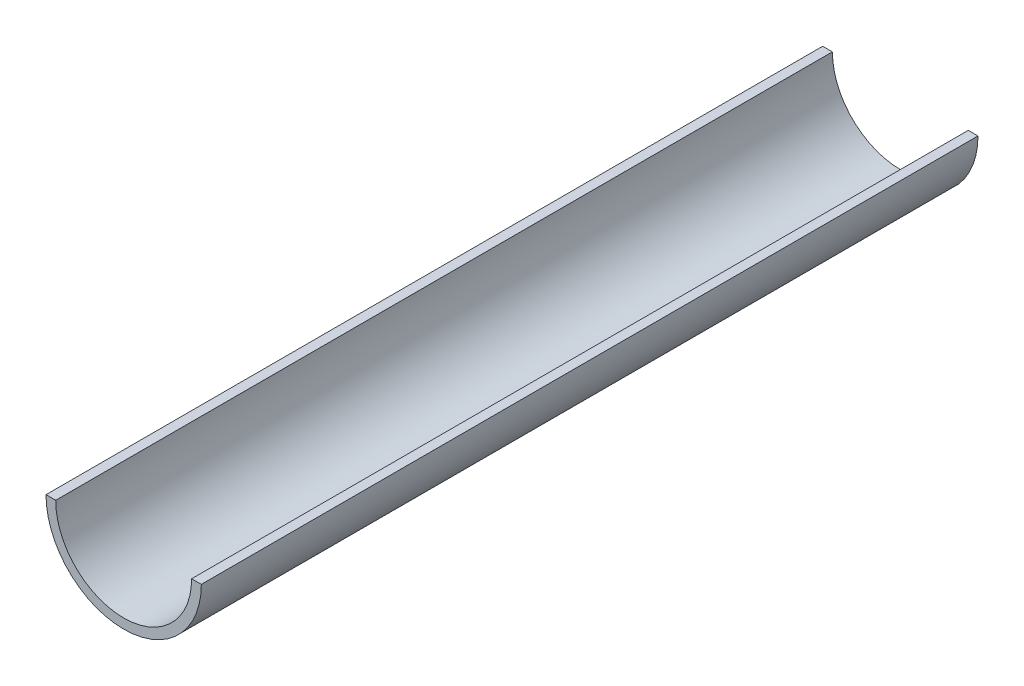
SolidWorks part; units mm, degrees
material "Acrylic (Medium-high impact)"
ref_plane "Front Plane" through (0, 0, 0) normal (0, 0, 1) x (1, 0, 0)
ref_plane "Top Plane" through (0, 0, 0) normal (0, 1, 0) x (1, 0, 0)
ref_plane "Right Plane" through (0, 0, 0) normal (1, 0, 0) x (0, 0, -1)
sketch "Sketch1" plane through (0, 0, 0) normal (0, 0, 1) x (1, 0, 0)
  circle A0 centre (0, 0) radius 25.4
  circle A1 centre (0, 0) radius 22.225
  dimension "D1" = 50.8
  dimension "D2" = 44.45
extrude "Boss-Extrude1" add sketch "Sketch1" along normal blind 914.4
sketch "Sketch2" plane through (0, 0, 0) normal (0, 0, -1) x (-1, 0, 0)
  circle A0 centre (0, 0) radius 25.4 construction
  circle A1 centre (0, 0) radius 25.4
extrude "Cut-Extrude1" cut sketch "Sketch2" against normal through all from offset 254 offset against normal yes
ref_plane "Plane1" through (0, -25.4, 0) normal (0, -1, 0) x (-1, 0, 0)
ref_plane "Plane3" through (0, -22.225, 0) normal (0, 1, 0) x (1, 0, 0)
ref_plane "Plane2" through (0, 0, 15.875) normal (0, 0, -1) x (-1, 0, 0)
sketch "Sketch4" plane through (0, 0, 0) normal (0, 0, 1) x (1, 0, 0)
  line L0 (-25.4, 0) -> (25.4, 0)
  circle A0 centre (0, 0) radius 25.4 construction
  arc A1 (25.4, 0) -> (-25.4, 0) centre (0, 0) ccw
extrude "Cut-Extrude3" cut sketch "Sketch4" along normal through all
